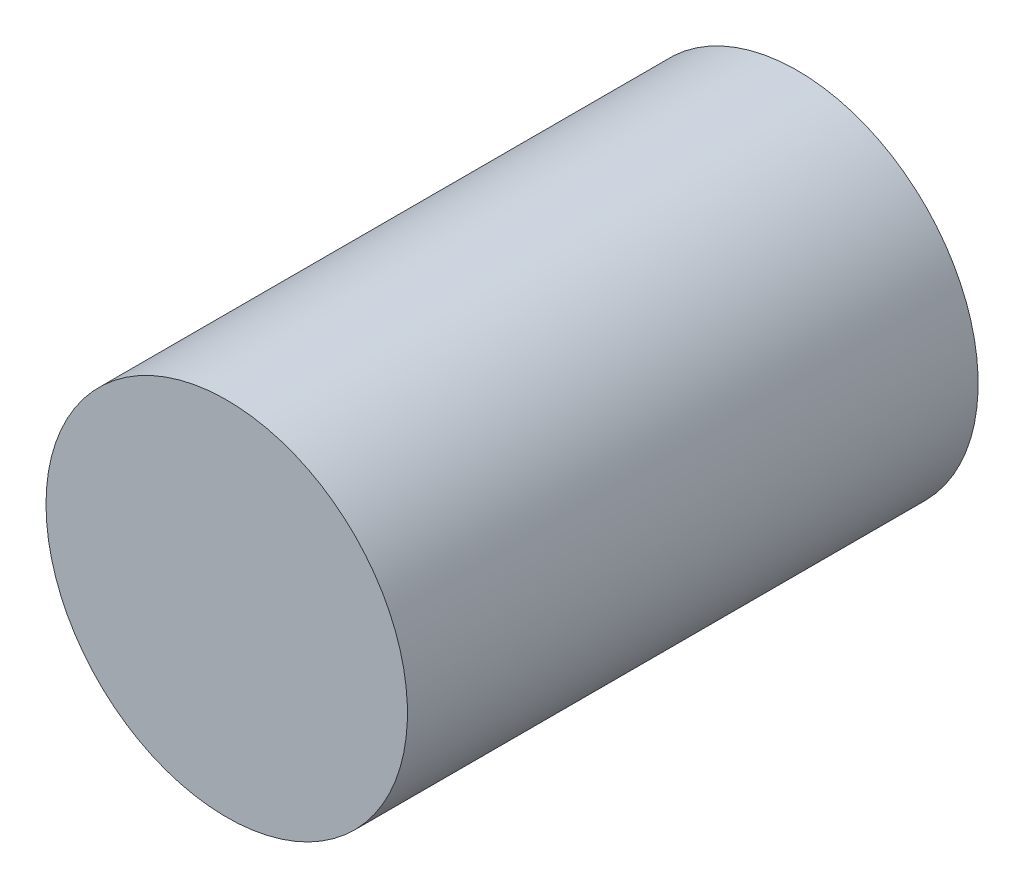
SolidWorks part; units mm, degrees
ref_plane "Front Plane" through (0, 0, 0) normal (0, 0, 1) x (1, 0, 0)
ref_plane "Top Plane" through (0, 0, 0) normal (0, 1, 0) x (1, 0, 0)
ref_plane "Right Plane" through (0, 0, 0) normal (1, 0, 0) x (0, 0, -1)
sketch "Sketch1" plane through (0, 0, 0) normal (0, 0, 1) x (1, 0, 0)
  circle A0 centre (-12.4312, 18.1884) radius 12.065
extrude "Boss-Extrude1" add sketch "Sketch1" along normal blind 38.1
